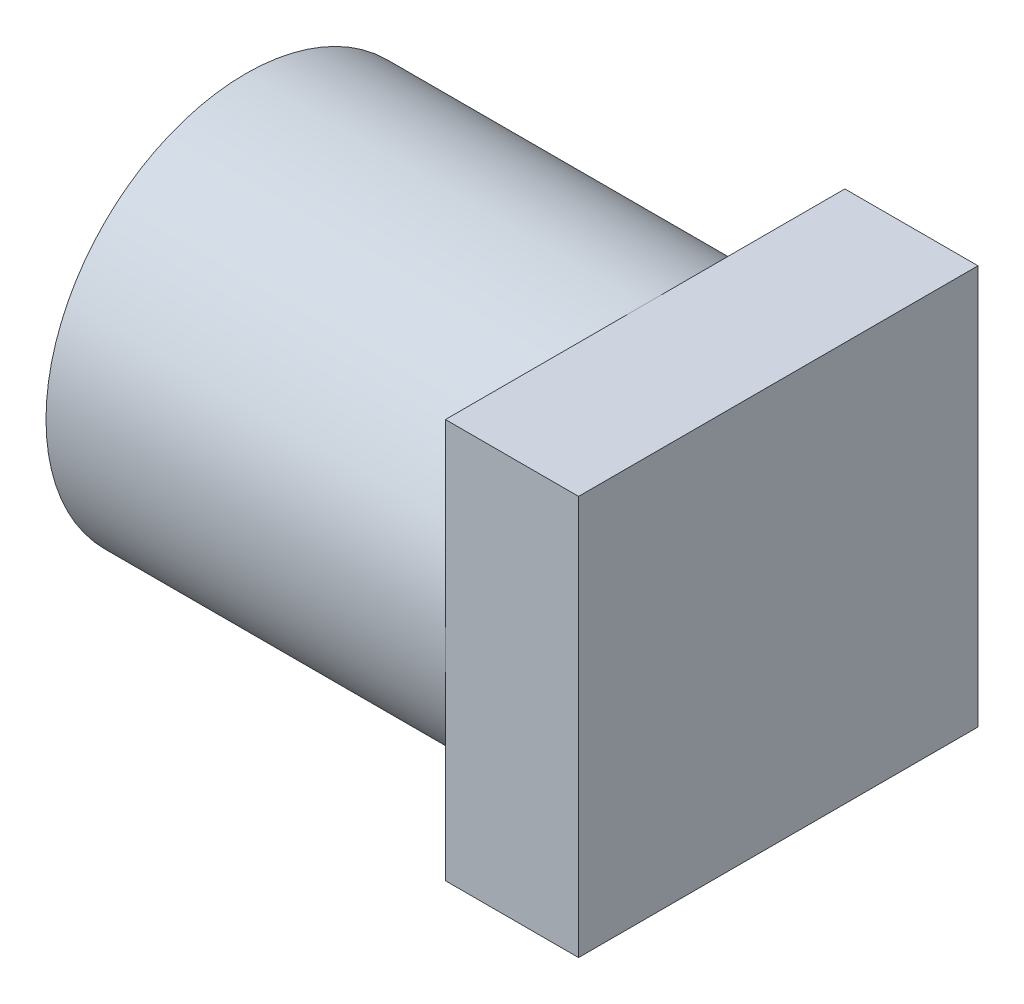
SolidWorks part; units mm, degrees
ref_plane "Front Plane" through (0, 0, 0) normal (0, 0, 1) x (1, 0, 0)
ref_plane "Top Plane" through (0, 0, 0) normal (0, 1, 0) x (1, 0, 0)
ref_plane "Right Plane" through (0, 0, 0) normal (1, 0, 0) x (0, 0, -1)
sketch "Sketch1" plane through (0, 0, 0) normal (1, 0, 0) x (0, 0, -1)
  circle A0 centre (0, 0) radius 15
  dimension "D1" = 30
extrude "Boss-Extrude1" add sketch "Sketch1" along normal blind 30
sketch "Sketch2" plane through (30, 0, 0) normal (1, 0, 0) x (0, 0, -1)
  line L1 (-15, 15) -> (15, 15)
  line L2 (-15, 15) -> (-15, -15)
  line L3 (-15, -15) -> (15, -15)
  line L4 (15, 15) -> (15, -15)
  line L5 (-15, 15) -> (15, -15) construction
  line L6 (-15, -15) -> (15, 15) construction
  point P0 (0, 0)
  dimension "D1" = 30
  dimension "D2" = 30
extrude "Boss-Extrude2" add sketch "Sketch2" along normal blind 10
